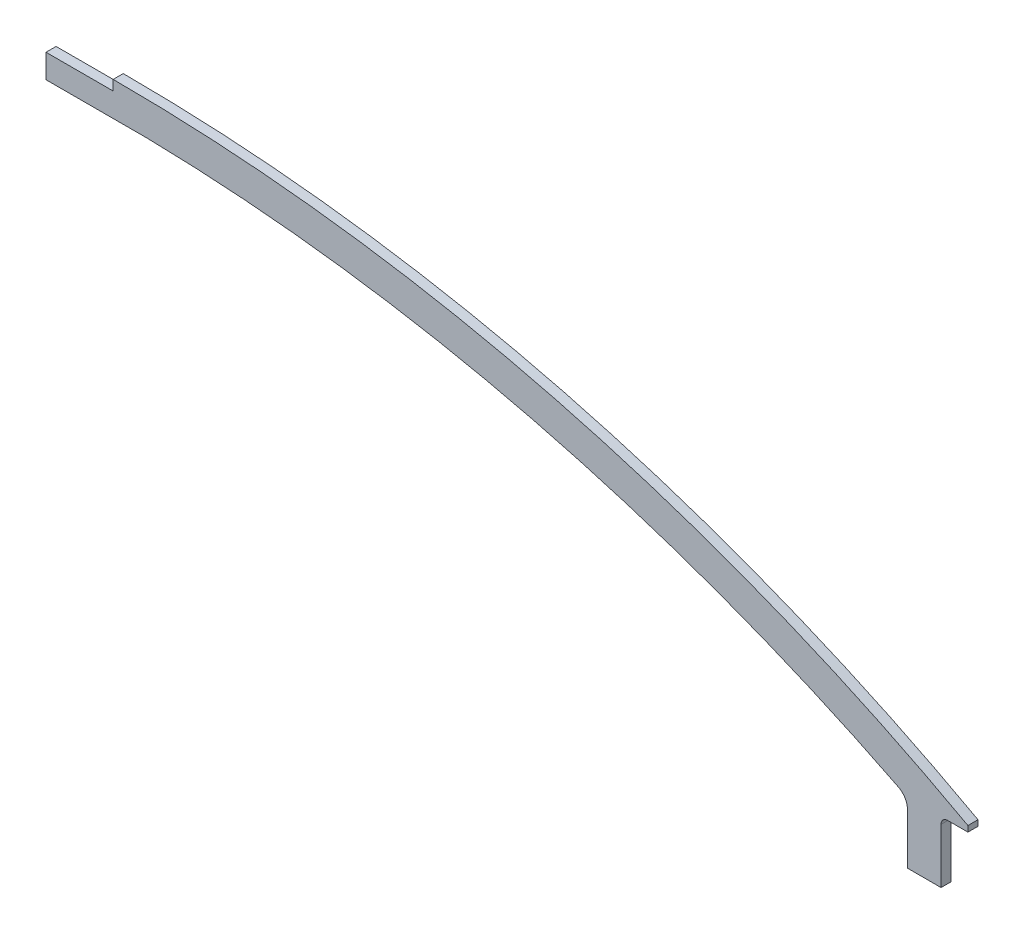
SolidWorks part; units mm, degrees
ref_plane "Front Plane" through (0, 0, 0) normal (0, 0, 1) x (1, 0, 0)
ref_plane "Top Plane" through (0, 0, 0) normal (0, 1, 0) x (1, 0, 0)
ref_plane "Right Plane" through (0, 0, 0) normal (1, 0, 0) x (0, 0, -1)
sketch "Sketch1" plane through (0, 0, 0) normal (0, 0, 1) x (1, 0, 0)
  line L0 (-45, 0) -> (45, 0) construction
  line L1 (300, -65.3534) -> (300, -85.3534)
  line L2 (-45, -150.7069) -> (45, -150.7069) construction
  line L3 (-45, 0) -> (-45, -150.7069) construction
  line L4 (45, 0) -> (45, -150.7069) construction
  line L5 (0, 0) -> (0, -150.7069)
  line L6 (45, 0) -> (0, 0)
  line L7 (0, -150.7069) -> (45, -150.7069)
  arc A0 (45, 0) -> (300, -65.3534) centre (45, -530.1639) cw
  arc A1 (-28.1177, 0) -> (35.3823, 0) centre (3.6323, -0.0236) cw construction
  arc A2 (45, -150.7069) -> (300, -85.3534) centre (45, 379.457) ccw
  point P4 (0, 0)
  dimension "D2" = 300
  dimension "D3" = 31.75
  dimension "D5" = 150.7069
  dimension "D1" = 90
  dimension "D4" = 20
sketch "Sketch2" plane through (0, 0, 0) normal (0, 0, 1) x (1, 0, 0)
  line L0 (299.5, -67.3534) -> (293.5, -67.3534)
  line L1 (291.5, -69.3534) -> (291.5, -85.6495)
  line L2 (54.9033, -10.5962) -> (25, -10.5962)
  line L3 (25, -10.5962) -> (25, -3.5)
  line L4 (300, -65.3534) -> (300, -85.3534) construction
  line L5 (300, -65.3534) -> (300, -85.3534) construction
  line L6 (299.5, -65.6495) -> (299.5, -67.3534)
  line L7 (291.5, -85.6495) -> (281.5, -85.6495)
  line L8 (45, -0.5) -> (45, -3.5)
  line L9 (45, 0) -> (45, -150.7069) construction
  line L10 (45, -3.5) -> (25, -3.5)
  line L11 (281.5, -85.6495) -> (281.5, -70.5046)
  line L12 (45, -0.5) -> (0.5, -0.5)
  line L13 (0.5, -0.5) -> (0.5, -150.2069)
  line L14 (0.5, -150.2069) -> (45, -150.2069)
  line L15 (299.5, -85.0574) -> (299.5, -65.6495)
  line L20 (55, -13.5) -> (25, -13.5) construction
  line L21 (55, -10.5962) -> (55, -13.5) construction
  arc A0 (278.749, -66.039) -> (55.0976, -10.5981) centre (45, -530.1639) ccw
  arc A1 (294.6951, -74.4195) -> (55, -10.5962) centre (45, -530.1639) ccw construction
  arc A2 (55.0976, -10.5981) -> (54.9033, -10.5962) centre (54.9033, -20.5962) ccw
  arc A3 (281.5, -70.5046) -> (278.749, -66.039) centre (276.5, -70.5046) ccw
  arc A4 (293.5, -67.3534) -> (291.5, -69.3534) centre (293.5, -69.3534) ccw
  arc A6 (45, -150.2069) -> (299.5, -85.0574) centre (45, 379.457) ccw
  arc A7 (299.5, -65.6495) -> (45, -0.5) centre (45, -530.1639) ccw
  arc A9 (299.5, -65.6495) -> (45, -0.5) centre (45, -530.1639) ccw
  point P26 (300, -75.3534)
  point P33 (291.5, -67.3534)
  dimension "D5" = 10
  dimension "D10" = 5
  dimension "D11" = 2
  dimension "D2" = 20
  dimension "D3" = 3
  dimension "D6" = 7.0962
  dimension "D7" = 8
  dimension "D8" = 8
  dimension "D9" = 10
  dimension "D12" = 20
  dimension "D1" = 0.5
  dimension "D4" = 10
extrude "Boss-Extrude1" add sketch "Sketch2" along normal mid plane 3
